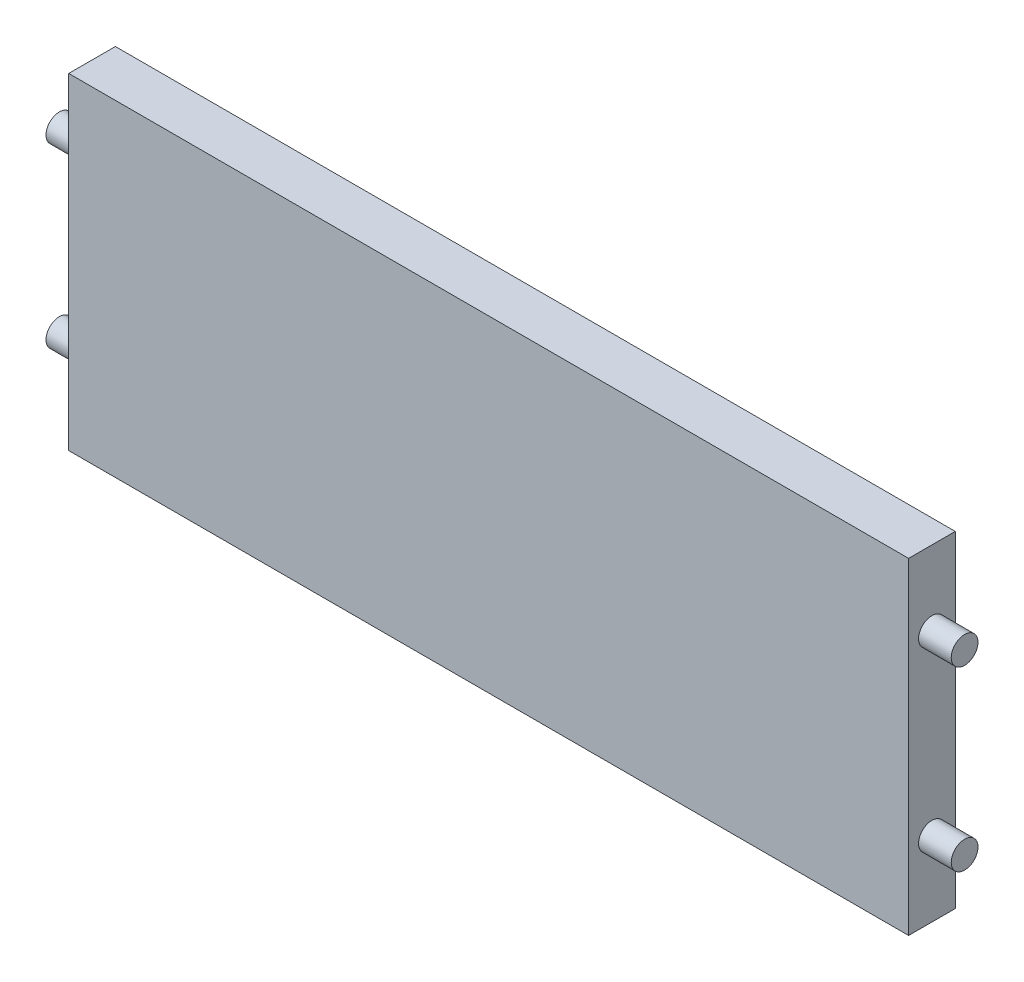
SolidWorks part; units mm, degrees
ref_plane "Front Plane" through (0, 0, 0) normal (0, 0, 1) x (1, 0, 0)
ref_plane "Top Plane" through (0, 0, 0) normal (0, 1, 0) x (1, 0, 0)
ref_plane "Right Plane" through (0, 0, 0) normal (1, 0, 0) x (0, 0, -1)
sketch "Sketch1" plane through (0, 0, 0) normal (0, 0, 1) x (1, 0, 0)
  line L0 (-45, -17.5) -> (45, -17.5)
  line L2 (-45, -17.5) -> (-45, 17.5)
  line L3 (-45, 17.5) -> (45, 17.5)
  line L4 (45, -17.5) -> (45, 17.5)
  line L5 (-45, -17.5) -> (45, 17.5) construction
  line L6 (-45, 17.5) -> (45, -17.5) construction
  line L12 (55, 0) -> (-55, 0) construction
  point P0 (0, 0)
  point P14 (27, 0)
  dimension "D1" = 90
  dimension "D2" = 35
  dimension "D3" = 27
extrude "Boss-Extrude1" add sketch "Sketch1" along normal blind 5
sketch "Sketch2" plane through (45, 0, 0) normal (1, 0, 0) x (0, 0, -1)
  line L0 (-2.5, 17.5) -> (-2.5, 9.5) construction
  line L1 (-5, 17.5) -> (0, 17.5) construction
  line L2 (2.75, 0) -> (-2.75, 0) construction
  circle A0 centre (-2.5, 9.5) radius 1.435
  circle A1 centre (-2.5, -9.5) radius 1.435
  dimension "D2" = 2.87
  dimension "D1" = 8
extrude "Boss-Extrude2" add sketch "Sketch2" along normal blind 3.5
sketch "Sketch3" plane through (-45, 0, 0) normal (-1, 0, 0) x (0, 0, 1)
  line L0 (2.5, 17.5) -> (2.5, 9.5) construction
  line L1 (5, 17.5) -> (0, 17.5) construction
  line L2 (2.75, 0) -> (-2.75, 0) construction
  circle A0 centre (2.5, 9.5) radius 1.435
  circle A1 centre (2.5, -9.5) radius 1.435
  dimension "D2" = 2.87
  dimension "D1" = 8
extrude "Boss-Extrude3" add sketch "Sketch3" along normal blind 3.5
